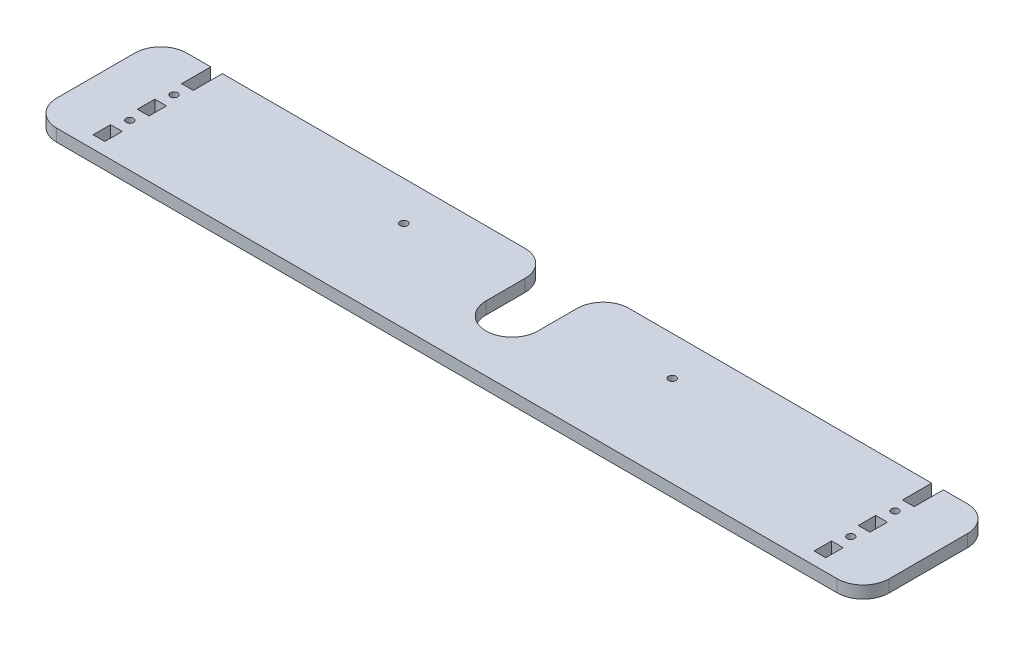
SolidWorks part; units mm, degrees
ref_plane "Front Plane" through (0, 0, 0) normal (0, 0, 1) x (1, 0, 0)
ref_plane "Top Plane" through (0, 0, 0) normal (0, 1, 0) x (1, 0, 0)
ref_plane "Right Plane" through (0, 0, 0) normal (1, 0, 0) x (0, 0, -1)
sketch "Sketch1" plane through (0, 0, 0) normal (0, 1, 0) x (1, 0, 0)
  line L0 (-65.5, 12.7) -> (65.5, 12.7) construction
  line L1 (-190.5, -31.75) -> (190.5, -31.75)
  line L2 (-203.2, -19.05) -> (-203.2, 19.05)
  line L3 (-190.5, 31.75) -> (-25.4, 31.75)
  line L4 (203.2, -19.05) -> (203.2, 19.05)
  line L5 (-203.2, -31.75) -> (203.2, 31.75) construction
  line L6 (-203.2, 31.75) -> (203.2, -31.75) construction
  line L7 (-12.7, 19.05) -> (-12.7, 0)
  line L8 (25.4, 31.75) -> (190.5, 31.75)
  line L9 (12.7, 0) -> (12.7, 19.05)
  line L10 (0, 0) -> (0, 12.7) construction
  line L11 (178.816, 31.75) -> (178.816, -31.75) construction
  line L12 (173.116, 26.035) -> (178.816, 26.035)
  line L13 (173.116, 26.035) -> (173.116, 17.526)
  line L14 (173.116, 17.526) -> (178.816, 17.526)
  line L15 (178.816, 26.035) -> (178.816, 17.526)
  line L16 (173.116, 4.445) -> (173.116, -4.064)
  line L17 (173.116, -4.064) -> (178.816, -4.064)
  line L18 (173.116, 4.445) -> (178.816, 4.445)
  line L19 (178.816, 4.445) -> (178.816, -4.064)
  line L20 (173.116, -17.145) -> (173.116, -25.654)
  line L21 (173.116, -25.654) -> (178.816, -25.654)
  line L22 (173.116, -17.145) -> (178.816, -17.145)
  line L23 (178.816, -17.145) -> (178.816, -25.654)
  line L24 (0, 56.8139) -> (0, -66.3049) construction
  line L25 (-178.816, 31.75) -> (-178.816, -31.75) construction
  line L26 (-178.816, -17.145) -> (-178.816, -25.654)
  line L27 (-173.116, -17.145) -> (-178.816, -17.145)
  line L28 (-173.116, -25.654) -> (-178.816, -25.654)
  line L29 (-173.116, -17.145) -> (-173.116, -25.654)
  line L30 (-178.816, 4.445) -> (-178.816, -4.064)
  line L31 (-173.116, 4.445) -> (-178.816, 4.445)
  line L32 (-173.116, -4.064) -> (-178.816, -4.064)
  line L33 (-173.116, 4.445) -> (-173.116, -4.064)
  line L34 (-178.816, 26.035) -> (-178.816, 17.526)
  line L35 (-173.116, 17.526) -> (-178.816, 17.526)
  line L36 (-173.116, 26.035) -> (-173.116, 17.526)
  line L37 (-173.116, 26.035) -> (-178.816, 26.035)
  line L38 (173.116, 26.035) -> (173.116, 31.75)
  line L39 (178.816, 26.035) -> (178.816, 31.75)
  line L40 (-173.116, 26.035) -> (-173.116, 31.75)
  line L41 (-178.816, 26.035) -> (-178.816, 31.75)
  line L42 (-178.816, 17.526) -> (-173.116, 4.445) construction
  line L43 (-173.116, -17.145) -> (-178.816, -4.064) construction
  line L44 (173.116, 17.526) -> (178.816, 4.445) construction
  line L45 (178.816, -4.064) -> (173.116, -17.145) construction
  circle A0 centre (-65.5, 12.7) radius 1.8288
  circle A1 centre (65.5, 12.7) radius 1.8288
  arc A2 (-12.7, 0) -> (12.7, 0) centre (0, 0) ccw
  arc A3 (-12.7, 19.05) -> (-25.4, 31.75) centre (-25.4, 19.05) ccw
  arc A4 (12.7, 19.05) -> (25.4, 31.75) centre (25.4, 19.05) cw
  arc A5 (190.5, 31.75) -> (203.2, 19.05) centre (190.5, 19.05) cw
  arc A6 (190.5, -31.75) -> (203.2, -19.05) centre (190.5, -19.05) ccw
  arc A7 (-190.5, -31.75) -> (-203.2, -19.05) centre (-190.5, -19.05) cw
  arc A8 (-203.2, 19.05) -> (-190.5, 31.75) centre (-190.5, 19.05) cw
  circle A9 centre (-175.966, 10.9855) radius 1.778
  circle A10 centre (-175.966, -10.6045) radius 1.778
  circle A11 centre (175.966, -10.6045) radius 1.778
  circle A12 centre (175.966, 10.9855) radius 1.778
  point P0 (0, 0)
  point P53 (12.7, 31.75)
  dimension "D3" = 3.6576
  dimension "D14" = 12.7
  dimension "D15" = 3.556
  dimension "D1" = 406.4
  dimension "D2" = 63.5
  dimension "D4" = 131
  dimension "D5" = 25.4
  dimension "D6" = 31.75
  dimension "D7" = 19.05
  dimension "D8" = 8.509
  dimension "D9" = 5.7
  dimension "D10" = 24.384
  dimension "D11" = 5.715
  dimension "D13" = 13.081
  dimension "D12" = 3
extrude "Boss-Extrude1" add sketch "Sketch1" along normal blind 6 contours A2 L7 L3 L40 L36 L35 L34 L41 L2 L1 L4 L8 L39 L15 L14 L13 L38 L9 A1 A0 L31 L33 L32 L30 L22 L23 L21 L20 L18 L19 L17 L16 L27 L29 L28 L26
